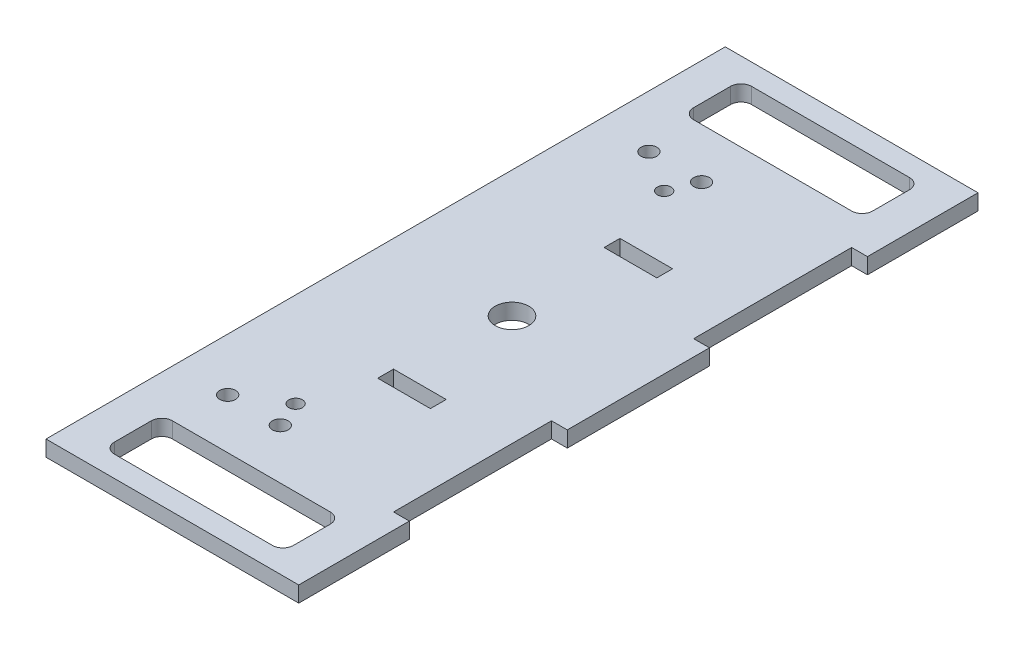
SolidWorks part; units mm, degrees
material "Balsa"
ref_plane "Front Plane" through (0, 0, 0) normal (0, 0, 1) x (1, 0, 0)
ref_plane "Top Plane" through (0, 0, 0) normal (0, 1, 0) x (1, 0, 0)
ref_plane "Right Plane" through (0, 0, 0) normal (1, 0, 0) x (0, 0, -1)
sketch "Sketch1" plane through (0, 0, 0) normal (0, 1, 0) x (1, 0, 0)
  line L0 (0, 0) -> (0, 106.5) construction
  line L1 (-24, 106.5) -> (24, 106.5)
  line L2 (-24, 106.5) -> (-24, -106.5)
  line L3 (-24, -106.5) -> (24, -106.5)
  line L4 (24, 106.5) -> (24, -106.5)
  line L5 (0, 0) -> (24, 0) construction
  circle A0 centre (0, 0) radius 3.2
  dimension "D3" = 6.4
  dimension "D1" = 213
  dimension "D2" = 48
extrude "Boss-Extrude1" add sketch "Sketch1" along normal blind 3
sketch "Sketch2" plane through (0, 3, 0) normal (0, 1, 0) x (1, 0, 0)
  line L1 (24, -106.5) -> (24, 106.5) construction
  line L2 (21, 85.5) -> (24, 85.5)
  line L3 (21, 85.5) -> (21, 64.5)
  line L4 (21, 64.5) -> (24, 64.5)
  line L5 (24, 85.5) -> (24, 64.5)
  line L6 (0, 0) -> (24, 0) construction
  line L7 (21, 43.5) -> (24, 43.5)
  line L8 (21, 43.5) -> (21, 13.5)
  line L9 (21, 13.5) -> (24, 13.5)
  line L10 (24, 43.5) -> (24, 13.5)
  line L12 (24, 106.5) -> (-24, 106.5) construction
  line L13 (24, -43.5) -> (24, -13.5)
  line L14 (21, -13.5) -> (24, -13.5)
  line L15 (21, -43.5) -> (21, -13.5)
  line L16 (21, -43.5) -> (24, -43.5)
  line L17 (24, -85.5) -> (24, -64.5)
  line L18 (21, -64.5) -> (24, -64.5)
  line L19 (21, -85.5) -> (21, -64.5)
  line L20 (21, -85.5) -> (24, -85.5)
  dimension "D1" = 21
  dimension "D2" = 30
  dimension "D3" = 21
  dimension "D4" = 21
  dimension "D5" = 3
extrude "Cut-Extrude1" cut sketch "Sketch2" against normal through all
sketch "Sketch3" plane through (0, 3, 0) normal (0, 1, 0) x (1, 0, 0)
  line L1 (-2.5, -23) -> (7.5, -23)
  line L2 (-2.5, -23) -> (-2.5, -20)
  line L3 (-2.5, -20) -> (7.5, -20)
  line L4 (7.5, -23) -> (7.5, -20)
  line L5 (-2.5, 20) -> (7.5, 20)
  line L6 (-2.5, 20) -> (-2.5, 23)
  line L7 (-2.5, 23) -> (7.5, 23)
  line L8 (7.5, 20) -> (7.5, 23)
extrude "Cut-Extrude2" cut sketch "Sketch3" against normal through all
sketch "Sketch4" plane through (0, 3, 0) normal (0, 1, 0) x (1, 0, 0)
  line L0 (24, 0) -> (-24, 0) construction
  line L1 (24, -13.5) -> (24, 13.5) construction
  line L2 (-24, 106.5) -> (-24, -106.5) construction
  circle A0 centre (-6.1, -35) radius 1.3
  circle A1 centre (-6.1, 35) radius 1.3
  dimension "D1" = 2.6
extrude "Cut-Extrude3" cut sketch "Sketch4" against normal through all
sketch "Sketch5" plane through (0, 3, 0) normal (0, 1, 0) x (1, 0, 0)
  line L0 (24, 64.5) -> (-24, 64.5)
  line L1 (-24, 106.5) -> (-24, -106.5) construction
  line L2 (-24, 64.5) -> (-24, 106.5)
  line L3 (-24, 106.5) -> (24, 106.5)
  line L4 (24, 106.5) -> (24, 64.5)
  line L5 (24, -64.5) -> (-24, -64.5)
  line L6 (-24, -64.5) -> (-24, -106.5)
  line L7 (-24, -106.5) -> (24, -106.5) construction
  line L8 (-24, -106.5) -> (24, -106.5)
  line L9 (24, -106.5) -> (24, -64.5)
extrude "Cut-Extrude4" cut sketch "Sketch5" against normal through all
sketch "Sketch6" plane through (0, 3, 0) normal (0, 1, 0) x (1, 0, 0)
  line L0 (-24, 64.5) -> (24, 64.5) construction
  line L1 (-17, 60.5) -> (17, 60.5)
  line L2 (-17, 60.5) -> (-17, 49.5)
  line L3 (-17, 49.5) -> (17, 49.5)
  line L4 (17, 60.5) -> (17, 49.5)
  line L5 (24, 43.5) -> (24, 64.5) construction
  line L6 (-24, 64.5) -> (-24, -64.5) construction
  line L7 (24, 43.5) -> (21, 43.5) construction
  dimension "D1" = 4
  dimension "D2" = 7
  dimension "D3" = 7
  dimension "D4" = 6
extrude "Cut-Extrude5" cut sketch "Sketch6" against normal through all
fillet "Fillet1" radius 2 4 edges at (-17, 1.5, -49.5) (17, 1.5, -49.5) (17, 1.5, -60.5) (-17, 1.5, -60.5)
mirror "Mirror1" about plane through (0, 0, 0) normal (0, 0, 1) of "Cut-Extrude5", "Fillet1"
sketch "Sketch7" plane through (0, 3, 0) normal (0, 1, 0) x (1, 0, 0)
  circle A0 centre (-14, -40) radius 1.5
  circle A1 centre (-4, -40) radius 1.5
  circle A2 centre (-4, -40) radius 1.85 construction
  dimension "D1" = 3
  dimension "D2" = 3
extrude "Cut-Extrude6" cut sketch "Sketch7" against normal through all
mirror "Mirror2" about plane through (0, 0, 0) normal (0, 0, 1) of "Cut-Extrude6"
